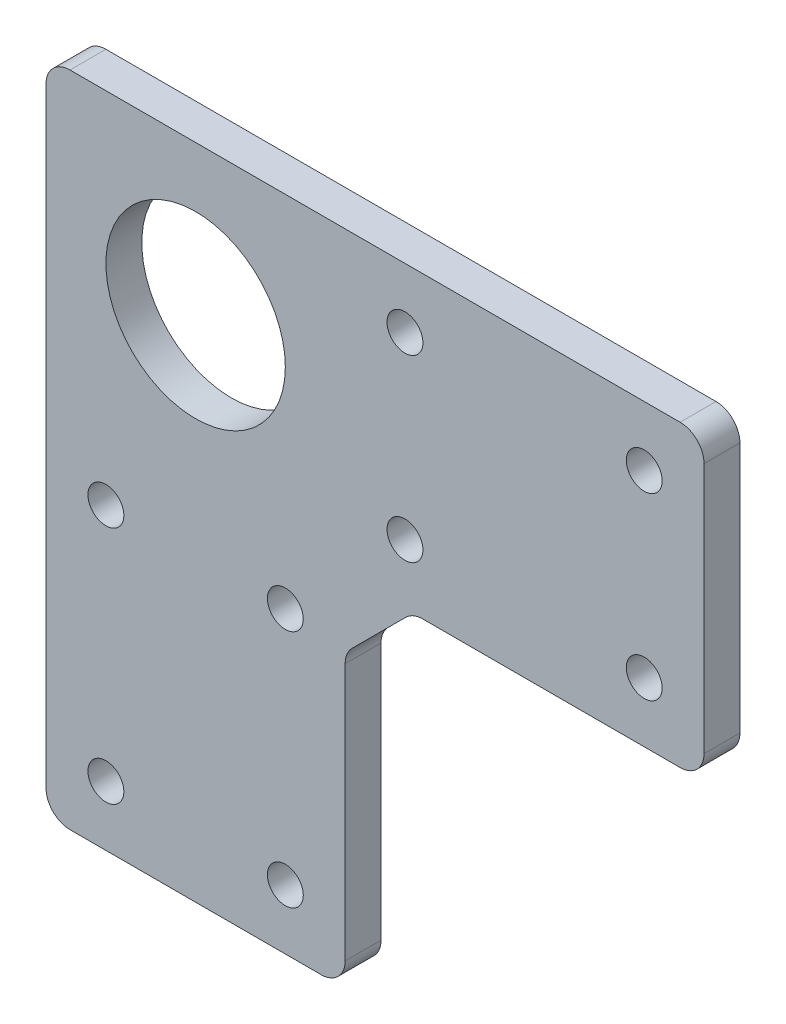
SolidWorks part; units mm, degrees
material "Thornel Mat VMA"
ref_plane "前视基准面" through (0, 0, 0) normal (0, 0, 1) x (1, 0, 0)
ref_plane "上视基准面" through (0, 0, 0) normal (0, 1, 0) x (1, 0, 0)
ref_plane "右视基准面" through (0, 0, 0) normal (1, 0, 0) x (0, 0, -1)
sketch "草图1" plane through (0, 0, 0) normal (0, 0, 1) x (1, 0, 0)
  line L1 (0, 0) -> (25, 0)
  line L2 (0, 0) -> (0, -30)
  line L3 (0, -30) -> (25, -30)
  line L4 (25, 0) -> (25, -30)
  line L5 (0, 0) -> (55, 0)
  line L6 (0, 0) -> (0, 25)
  line L7 (0, 25) -> (55, 25)
  line L8 (55, 0) -> (55, 25)
  dimension "D1" = 25
  dimension "D2" = 25
  dimension "D3" = 30
  dimension "D4" = 30
extrude "凸台-拉伸1" add sketch "草图1" along normal mid plane 3 contours L4 L1 L2 L3 | L5 L8 L7 L6 L1
sketch "草图2" plane through (0, 0, 1.5) normal (0, 0, 1) x (1, 0, 0)
  line L0 (0, -30) -> (25, -30) construction
  line L1 (5, -25) -> (20, -25) construction
  line L2 (5, -25) -> (5, -5) construction
  line L3 (5, -5) -> (20, -5) construction
  line L4 (20, -25) -> (20, -5) construction
  line L5 (12.5, -5) -> (12.5, -25) construction
  line L6 (5, -15) -> (20, -15) construction
  line L8 (25, 0) -> (55, 0) construction
  line L9 (25, 0) -> (25, -30) construction
  line L10 (12.5, -25) -> (12.5, -30) construction
  line L11 (0, 25) -> (25, 0) construction
  line L12 (50, 12.5) -> (55, 12.5) construction
  line L13 (40, 20) -> (40, 5) construction
  line L14 (30, 12.5) -> (50, 12.5) construction
  line L15 (50, 5) -> (30, 5) construction
  line L16 (30, 20) -> (30, 5) construction
  line L17 (50, 20) -> (30, 20) construction
  line L18 (50, 20) -> (50, 5) construction
  circle A0 centre (20, -25) radius 1.5
  circle A1 centre (5, -25) radius 1.5
  circle A2 centre (5, -5) radius 1.5
  circle A3 centre (20, -5) radius 1.5
  circle A4 centre (30, 5) radius 1.5
  circle A5 centre (30, 20) radius 1.5
  circle A6 centre (50, 20) radius 1.5
  circle A7 centre (50, 5) radius 1.5
  point P0 (12.5, -15)
  point P30 (40, 12.5)
  dimension "D4" = 3
  dimension "D1" = 5
  dimension "D2" = 5
  dimension "D3" = 5
extrude "切除-拉伸1" cut sketch "草图2" against normal mid plane 43
sketch "草图3" plane through (0, 0, 1.5) normal (0, 0, 1) x (1, 0, 0)
  line L0 (0, 25) -> (27.8284, -2.8284) construction
  line L1 (25, -5.6569) -> (30.6569, 0)
  line L2 (25, 0) -> (55, 0) construction
  line L3 (30.6569, 0) -> (25, 0)
  line L4 (25, 0) -> (25, -5.6569)
  point P10 (27.8284, -2.8284)
  dimension "D1" = 4
extrude "凸台-拉伸2" add sketch "草图3" against normal up to surface (3 mm away) up to face at (6.5, -25, -1.5)
fillet "圆角1" radius 2 7 edges at (25, -30, 0) (0, -30, 0) (0, 25, 0) (55, 25, 0) (55, 0, 0) (25, -5.6569, 0) (30.6569, 0, 0)
sketch "草图4" plane through (0, 0, 1.5) normal (0, 0, 1) x (1, 0, 0)
  line L0 (12.5, 12.5) -> (55, 12.5) construction
  line L1 (55, 2) -> (55, 23) construction
  line L2 (12.5, 12.5) -> (12.5, -30) construction
  line L3 (2, -30) -> (23, -30) construction
  circle A0 centre (12.5, 12.5) radius 7.5
  dimension "D1" = 15
extrude "切除-拉伸2" cut sketch "草图4" against normal blind 10
equation "\"D2@草图1\"=\"D1@草图1\""
